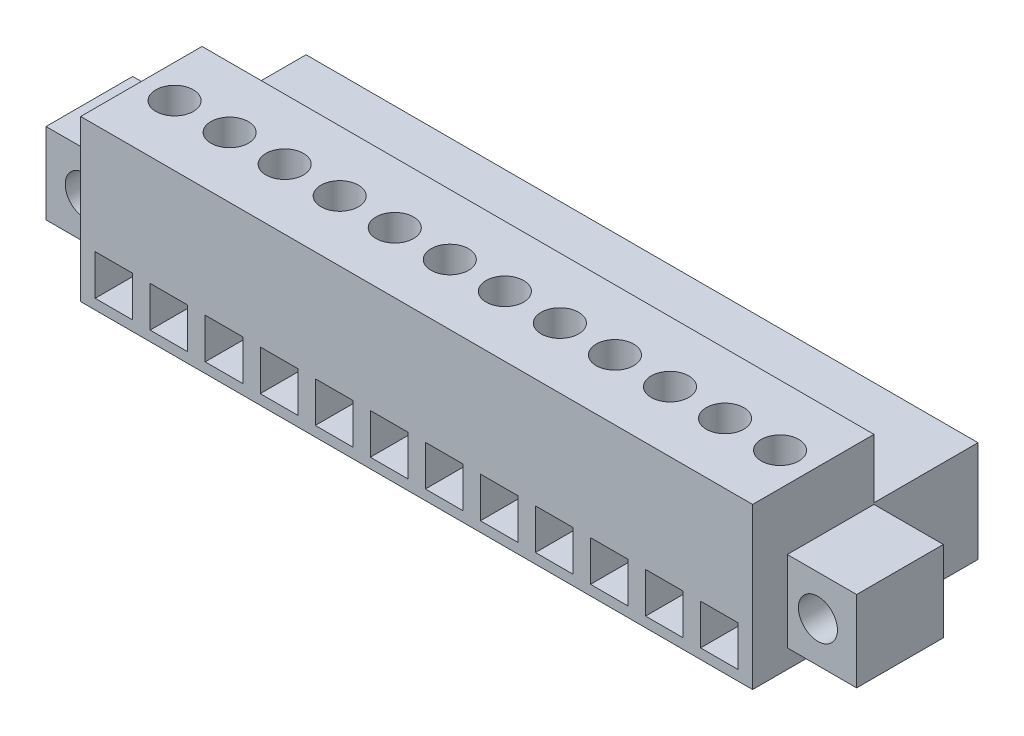
SolidWorks part; units mm, degrees
ref_plane "Front Plane" through (0, 0, 0) normal (0, 0, 1) x (1, 0, 0)
ref_plane "Top Plane" through (0, 0, 0) normal (0, 1, 0) x (1, 0, 0)
ref_plane "Right Plane" through (0, 0, 0) normal (1, 0, 0) x (0, 0, -1)
ref_plane "PL mating face" through (0, 0, 3) normal (0, 0, 1) x (1, 0, 0)
sketch "SK Body" plane through (0, 0, 3) normal (0, 0, 1) x (1, 0, 0)
  line L0 (-23.255, -4.1) -> (23.255, -4.1)
  line L1 (23.255, -4.1) -> (23.255, 7)
  line L2 (23.255, 7) -> (-23.255, 7)
  line L3 (-23.255, 7) -> (-23.255, -4.1)
extrude "Body" add sketch "SK Body" along normal blind 8.4
sketch "SK Flange ears" plane through (0, 0, 3) normal (0, 0, 1) x (1, 0, 0)
  line L0 (23.255, -2.8) -> (28.055, -2.8)
  line L1 (28.055, -2.8) -> (28.055, 2.8)
  line L2 (28.055, 2.8) -> (23.255, 2.8)
  line L3 (23.255, 2.8) -> (23.255, -2.8)
  line L4 (-28.055, -2.8) -> (-23.255, -2.8)
  line L5 (-23.255, -2.8) -> (-23.255, 2.8)
  line L6 (-23.255, 2.8) -> (-28.055, 2.8)
  line L7 (-28.055, 2.8) -> (-28.055, -2.8)
extrude "Flange ears" add sketch "SK Flange ears" along normal blind 6
sketch "SK Nose" plane through (0, 0, 3) normal (0, 0, 1) x (1, 0, 0)
  line L0 (-23.255, -4.1) -> (23.255, -4.1)
  line L1 (23.255, -4.1) -> (23.255, 2.9)
  line L2 (23.255, 2.9) -> (-23.255, 2.9)
  line L3 (-23.255, 2.9) -> (-23.255, -4.1)
extrude "Nose" add sketch "SK Nose" against normal blind 7.2
sketch "SK Flange screw holes" plane through (0, 0, 0) normal (0, 0, 1) x (1, 0, 0)
  circle A0 centre (-25.375, 0) radius 1.35
  circle A1 centre (25.375, 0) radius 1.35
extrude "Flange screw holes" cut sketch "SK Flange screw holes" against normal through all and the other way through all
ref_plane "PL wire face" through (0, 0, 11.4) normal (0, 0, 1) x (1, 0, 0)
sketch "SK Wire entries" plane through (0, 0, 11.4) normal (0, 0, 1) x (1, 0, 0)
  line L0 (-22.255, -3.4) -> (-19.655, -3.4)
  line L1 (-19.655, -3.4) -> (-19.655, -0.6)
  line L2 (-19.655, -0.6) -> (-22.255, -0.6)
  line L3 (-22.255, -0.6) -> (-22.255, -3.4)
  line L4 (-18.445, -3.4) -> (-15.845, -3.4)
  line L5 (-15.845, -3.4) -> (-15.845, -0.6)
  line L6 (-15.845, -0.6) -> (-18.445, -0.6)
  line L7 (-18.445, -0.6) -> (-18.445, -3.4)
  line L8 (-14.635, -3.4) -> (-12.035, -3.4)
  line L9 (-12.035, -3.4) -> (-12.035, -0.6)
  line L10 (-12.035, -0.6) -> (-14.635, -0.6)
  line L11 (-14.635, -0.6) -> (-14.635, -3.4)
  line L12 (-10.825, -3.4) -> (-8.225, -3.4)
  line L13 (-8.225, -3.4) -> (-8.225, -0.6)
  line L14 (-8.225, -0.6) -> (-10.825, -0.6)
  line L15 (-10.825, -0.6) -> (-10.825, -3.4)
  line L16 (-7.015, -3.4) -> (-4.415, -3.4)
  line L17 (-4.415, -3.4) -> (-4.415, -0.6)
  line L18 (-4.415, -0.6) -> (-7.015, -0.6)
  line L19 (-7.015, -0.6) -> (-7.015, -3.4)
  line L20 (-3.205, -3.4) -> (-0.605, -3.4)
  line L21 (-0.605, -3.4) -> (-0.605, -0.6)
  line L22 (-0.605, -0.6) -> (-3.205, -0.6)
  line L23 (-3.205, -0.6) -> (-3.205, -3.4)
  line L24 (0.605, -3.4) -> (3.205, -3.4)
  line L25 (3.205, -3.4) -> (3.205, -0.6)
  line L26 (3.205, -0.6) -> (0.605, -0.6)
  line L27 (0.605, -0.6) -> (0.605, -3.4)
  line L28 (4.415, -3.4) -> (7.015, -3.4)
  line L29 (7.015, -3.4) -> (7.015, -0.6)
  line L30 (7.015, -0.6) -> (4.415, -0.6)
  line L31 (4.415, -0.6) -> (4.415, -3.4)
  line L32 (8.225, -3.4) -> (10.825, -3.4)
  line L33 (10.825, -3.4) -> (10.825, -0.6)
  line L34 (10.825, -0.6) -> (8.225, -0.6)
  line L35 (8.225, -0.6) -> (8.225, -3.4)
  line L36 (12.035, -3.4) -> (14.635, -3.4)
  line L37 (14.635, -3.4) -> (14.635, -0.6)
  line L38 (14.635, -0.6) -> (12.035, -0.6)
  line L39 (12.035, -0.6) -> (12.035, -3.4)
  line L40 (15.845, -3.4) -> (18.445, -3.4)
  line L41 (18.445, -3.4) -> (18.445, -0.6)
  line L42 (18.445, -0.6) -> (15.845, -0.6)
  line L43 (15.845, -0.6) -> (15.845, -3.4)
  line L44 (19.655, -3.4) -> (22.255, -3.4)
  line L45 (22.255, -3.4) -> (22.255, -0.6)
  line L46 (22.255, -0.6) -> (19.655, -0.6)
  line L47 (19.655, -0.6) -> (19.655, -3.4)
extrude "Wire entries" cut sketch "SK Wire entries" against normal blind 6
ref_plane "PL nose tip" through (0, 0, -4.2) normal (0, 0, 1) x (1, 0, 0)
sketch "SK Contact openings" plane through (0, 0, -4.2) normal (0, 0, 1) x (1, 0, 0)
  line L0 (-21.755, -1.4) -> (-20.155, -1.4)
  line L1 (-20.155, -1.4) -> (-20.155, 0.2)
  line L2 (-20.155, 0.2) -> (-21.755, 0.2)
  line L3 (-21.755, 0.2) -> (-21.755, -1.4)
  line L4 (-17.945, -1.4) -> (-16.345, -1.4)
  line L5 (-16.345, -1.4) -> (-16.345, 0.2)
  line L6 (-16.345, 0.2) -> (-17.945, 0.2)
  line L7 (-17.945, 0.2) -> (-17.945, -1.4)
  line L8 (-14.135, -1.4) -> (-12.535, -1.4)
  line L9 (-12.535, -1.4) -> (-12.535, 0.2)
  line L10 (-12.535, 0.2) -> (-14.135, 0.2)
  line L11 (-14.135, 0.2) -> (-14.135, -1.4)
  line L12 (-10.325, -1.4) -> (-8.725, -1.4)
  line L13 (-8.725, -1.4) -> (-8.725, 0.2)
  line L14 (-8.725, 0.2) -> (-10.325, 0.2)
  line L15 (-10.325, 0.2) -> (-10.325, -1.4)
  line L16 (-6.515, -1.4) -> (-4.915, -1.4)
  line L17 (-4.915, -1.4) -> (-4.915, 0.2)
  line L18 (-4.915, 0.2) -> (-6.515, 0.2)
  line L19 (-6.515, 0.2) -> (-6.515, -1.4)
  line L20 (-2.705, -1.4) -> (-1.105, -1.4)
  line L21 (-1.105, -1.4) -> (-1.105, 0.2)
  line L22 (-1.105, 0.2) -> (-2.705, 0.2)
  line L23 (-2.705, 0.2) -> (-2.705, -1.4)
  line L24 (1.105, -1.4) -> (2.705, -1.4)
  line L25 (2.705, -1.4) -> (2.705, 0.2)
  line L26 (2.705, 0.2) -> (1.105, 0.2)
  line L27 (1.105, 0.2) -> (1.105, -1.4)
  line L28 (4.915, -1.4) -> (6.515, -1.4)
  line L29 (6.515, -1.4) -> (6.515, 0.2)
  line L30 (6.515, 0.2) -> (4.915, 0.2)
  line L31 (4.915, 0.2) -> (4.915, -1.4)
  line L32 (8.725, -1.4) -> (10.325, -1.4)
  line L33 (10.325, -1.4) -> (10.325, 0.2)
  line L34 (10.325, 0.2) -> (8.725, 0.2)
  line L35 (8.725, 0.2) -> (8.725, -1.4)
  line L36 (12.535, -1.4) -> (14.135, -1.4)
  line L37 (14.135, -1.4) -> (14.135, 0.2)
  line L38 (14.135, 0.2) -> (12.535, 0.2)
  line L39 (12.535, 0.2) -> (12.535, -1.4)
  line L40 (16.345, -1.4) -> (17.945, -1.4)
  line L41 (17.945, -1.4) -> (17.945, 0.2)
  line L42 (17.945, 0.2) -> (16.345, 0.2)
  line L43 (16.345, 0.2) -> (16.345, -1.4)
  line L44 (20.155, -1.4) -> (21.755, -1.4)
  line L45 (21.755, -1.4) -> (21.755, 0.2)
  line L46 (21.755, 0.2) -> (20.155, 0.2)
  line L47 (20.155, 0.2) -> (20.155, -1.4)
extrude "Contact openings" cut sketch "SK Contact openings" along normal blind 6.2
ref_plane "PL top face" through (0, 7, 0) normal (0, 1, 0) x (1, 0, 0)
sketch "SK Clamp screw holes" plane through (0, 7, 0) normal (0, 1, 0) x (1, 0, 0)
  circle A0 centre (-20.955, -7.2) radius 1.3
  circle A1 centre (-17.145, -7.2) radius 1.3
  circle A2 centre (-13.335, -7.2) radius 1.3
  circle A3 centre (-9.525, -7.2) radius 1.3
  circle A4 centre (-5.715, -7.2) radius 1.3
  circle A5 centre (-1.905, -7.2) radius 1.3
  circle A6 centre (1.905, -7.2) radius 1.3
  circle A7 centre (5.715, -7.2) radius 1.3
  circle A8 centre (9.525, -7.2) radius 1.3
  circle A9 centre (13.335, -7.2) radius 1.3
  circle A10 centre (17.145, -7.2) radius 1.3
  circle A11 centre (20.955, -7.2) radius 1.3
extrude "Clamp screw holes" cut sketch "SK Clamp screw holes" against normal blind 3
